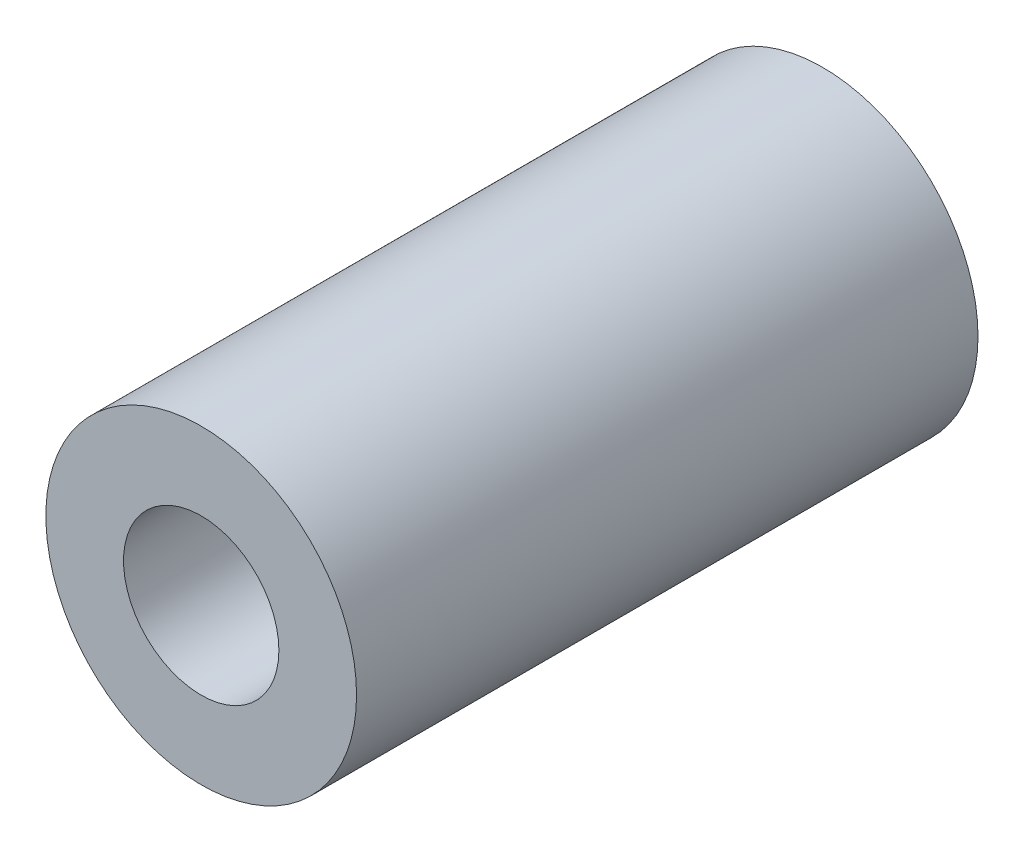
SolidWorks part; units mm, degrees
ref_plane "Front Plane" through (0, 0, 0) normal (0, 0, 1) x (1, 0, 0)
ref_plane "Top Plane" through (0, 0, 0) normal (0, 1, 0) x (1, 0, 0)
ref_plane "Right Plane" through (0, 0, 0) normal (1, 0, 0) x (0, 0, -1)
sketch "Sketch1" plane through (0, 0, 0) normal (0, 0, 1) x (1, 0, 0)
  circle A0 centre (0, 0) radius 6.35
  dimension "D1" = 12.7
extrude "Boss-Extrude1" add sketch "Sketch1" along normal blind 25.4
sketch "Sketch2" plane through (0, 0, 25.4) normal (0, 0, 1) x (1, 0, 0)
  circle A0 centre (0, 0) radius 3.175
  dimension "D1" = 6.35
extrude "Cut-Extrude1" cut sketch "Sketch2" against normal through all both and the other way through all
